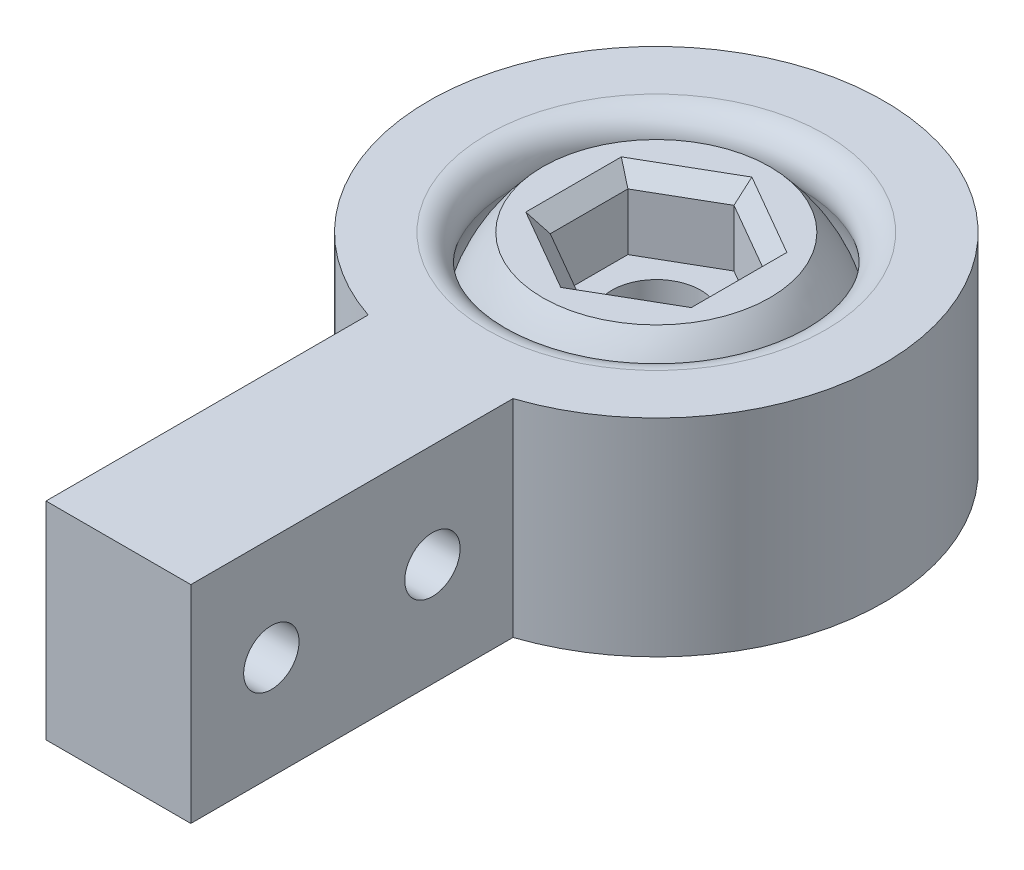
SolidWorks part; units mm, degrees
ref_plane "Front Plane" through (0, 0, 0) normal (0, 0, 1) x (1, 0, 0)
ref_plane "Top Plane" through (0, 0, 0) normal (0, 1, 0) x (1, 0, 0)
ref_plane "Right Plane" through (0, 0, 0) normal (1, 0, 0) x (0, 0, -1)
sketch "Sketch1" plane through (0, 0, 0) normal (0, 1, 0) x (1, 0, 0)
  circle A0 centre (0, 0) radius 4.2
  circle A1 centre (0, 0) radius 15.5
  circle A2 centre (0, 0) radius 25
  dimension "D1" = 8.4
  dimension "D2" = 31
  dimension "D3" = 50
extrude "Boss-Extrude1" add sketch "Sketch1" along normal mid plane 30 contours A2 A1 | A1 A0
sketch "Sketch2" plane through (0, 0, 0) normal (0, 1, 0) x (1, 0, 0)
  line L0 (0, 15.5) -> (0, -15.5)
  arc A0 (0, -15.5) -> (0, 15.5) centre (0, 0) ccw
  dimension "D1" = 31
revolve "Cut-Revolve3" cut sketch "Sketch2" angle 360 about L0
sketch "Sketch3" plane through (0, 15, 0) normal (0, 1, 0) x (1, 0, 0)
  circle A1 centre (0, 0) radius 25
  circle A2 centre (0, 0) radius 25
  dimension "D1" = 0
extrude "Cut-Extrude2" cut sketch "Sketch3" against normal blind 5
sketch "Sketch4" plane through (0, -15, 0) normal (0, -1, 0) x (1, 0, 0)
  circle A1 centre (0, 0) radius 25
  circle A2 centre (0, 0) radius 25
  dimension "D1" = 0
extrude "Cut-Extrude3" cut sketch "Sketch4" against normal blind 5
sketch "Sketch5" plane through (0, 0, 0) normal (0, 1, 0) x (1, 0, 0)
  line L0 (0, 14.85) -> (0, -14.85)
  arc A0 (0, -14.85) -> (0, 14.85) centre (0, 0) ccw
  dimension "D1" = 29.7
revolve "Revolve1" add sketch "Sketch5" angle 360 about L0
sketch "Sketch6" plane through (0, 10, 0) normal (0, 1, 0) x (1, 0, 0)
  circle A0 centre (0, 0) radius 25
extrude "Cut-Extrude4" cut sketch "Sketch6" along normal blind 5
sketch "Sketch7" plane through (0, -10, 0) normal (0, -1, 0) x (1, 0, 0)
  circle A1 centre (0, 0) radius 25
  circle A2 centre (0, 0) radius 25
  dimension "D1" = 0
extrude "Cut-Extrude5" cut sketch "Sketch7" along normal blind 5
sketch "Sketch8" plane through (0, 10, 0) normal (0, 1, 0) x (1, 0, 0)
  circle A0 centre (0, 0) radius 4.2
  dimension "D1" = 8.4
extrude "Cut-Extrude6" cut sketch "Sketch8" against normal blind 23
sketch "Sketch9" plane through (0, 10, 0) normal (0, 1, 0) x (1, 0, 0)
  line L0 (0, -25) -> (0, -55)
  line L1 (-10, -25) -> (-10, -55)
  line L2 (10, -25) -> (10, -55)
  line L3 (-10, -55) -> (10, -55)
  line L4 (10, -25) -> (10, -20.3933)
  line L5 (10, -20.3933) -> (-10, -20.3933)
  line L6 (-10, -20.3933) -> (-10, -25)
  circle A0 centre (0, 0) radius 25 construction
  circle M3 centre (0, 0) radius 25
  dimension "D1" = 30
  dimension "D2" = 10
  dimension "D3" = 10
extrude "Boss-Extrude2" add sketch "Sketch9" against normal up to surface (20 mm away) contours L6 L1 L3 L0 M3 | L2 L4 L0 L3 M3 up to face at (0, -10, -11.8427)
sketch "Sketch10" plane through (0, 10, 0) normal (0, 1, 0) x (1, 0, 0)
  line L6 (-7, -20.8567) -> (-7, -52)
  line L7 (-7, -52) -> (7, -52)
  line L8 (7, -52) -> (7, -20.8567)
  line L9 (-7, -20.8567) -> (-7, -52)
  line L10 (-7, -52) -> (7, -52)
  line L11 (7, -52) -> (7, -20.8567)
  line L12 (-10, -22.9129) -> (-10, -55)
  line L13 (-10, -55) -> (10, -55)
  line L14 (10, -55) -> (10, -22.9129)
  line L15 (-10, -22.9129) -> (-10, -55)
  line L16 (-10, -55) -> (10, -55)
  line L17 (10, -55) -> (10, -22.9129)
  arc A2 (7, -20.8567) -> (-7, -20.8567) centre (0, 0) ccw
  arc A3 (7, -20.8567) -> (-7, -20.8567) centre (0, 0) ccw
  arc A4 (10, -22.9129) -> (-10, -22.9129) centre (0, 0) ccw
  arc A5 (10, -22.9129) -> (-10, -22.9129) centre (0, 0) ccw
  dimension "D1" = 3
  dimension "D2" = 0
extrude "Cut-Extrude7" cut sketch "Sketch10" against normal blind 50
sketch "Sketch11" plane through (7, 0, 0) normal (1, 0, 0) x (0, 0, -1)
  line L0 (-52, 0) -> (-36.4283, 0)
  line L1 (-52, -10) -> (-52, 10) construction
  line L3 (-36.4283, 0) -> (-36.4283, 3.0153)
  circle A0 centre (-44.2142, 0) radius 2.675
  circle A1 centre (-28.6425, 0) radius 2.675
  dimension "D1" = 5.35
extrude "Cut-Extrude8" cut sketch "Sketch11" against normal through all both and the other way through all contours L0 A0 | L0 A0 | A1
fillet "Fillet1" radius 2.5 2 edges at (0, -10, -11.8427) (0, 10, 11.8427)
sketch "Sketch12" plane through (0, 10, 0) normal (0, 1, 0) x (1, 0, 0)
  line L1 (0, 7.5056) -> (-6.5, 3.7528)
  line L2 (-6.5, 3.7528) -> (-6.5, -3.7528)
  line L3 (-6.5, -3.7528) -> (0, -7.5056)
  line L4 (0, -7.5056) -> (6.5, -3.7528)
  line L5 (6.5, -3.7528) -> (6.5, 3.7528)
  line L6 (6.5, 3.7528) -> (0, 7.5056)
  circle A0 centre (0, 0) radius 6.5 construction
  dimension "D1" = 13
extrude "Cut-Extrude9" cut sketch "Sketch12" against normal blind 7
sketch "Sketch13" plane through (0, -10, 0) normal (0, -1, 0) x (1, 0, 0)
  circle A1 centre (0, 0) radius 7.621
extrude "Cut-Extrude10" cut sketch "Sketch13" against normal blind 7
sketch "Sketch14" plane through (0, -3, 0) normal (0, -1, 0) x (1, 0, 0)
  circle A0 centre (0, 0) radius 4.3
  dimension "D1" = 8.6
extrude "Cut-Extrude11" cut sketch "Sketch14" along normal through all both and the other way through all
chamfer "Chamfer1" distance 1.5 angle 45 6 edges at (3.25, 10, 5.6292) (-3.25, 10, 5.6292) (-6.5, 10, 0) (-3.25, 10, -5.6292) (3.25, 10, -5.6292) (6.5, 10, 0)
